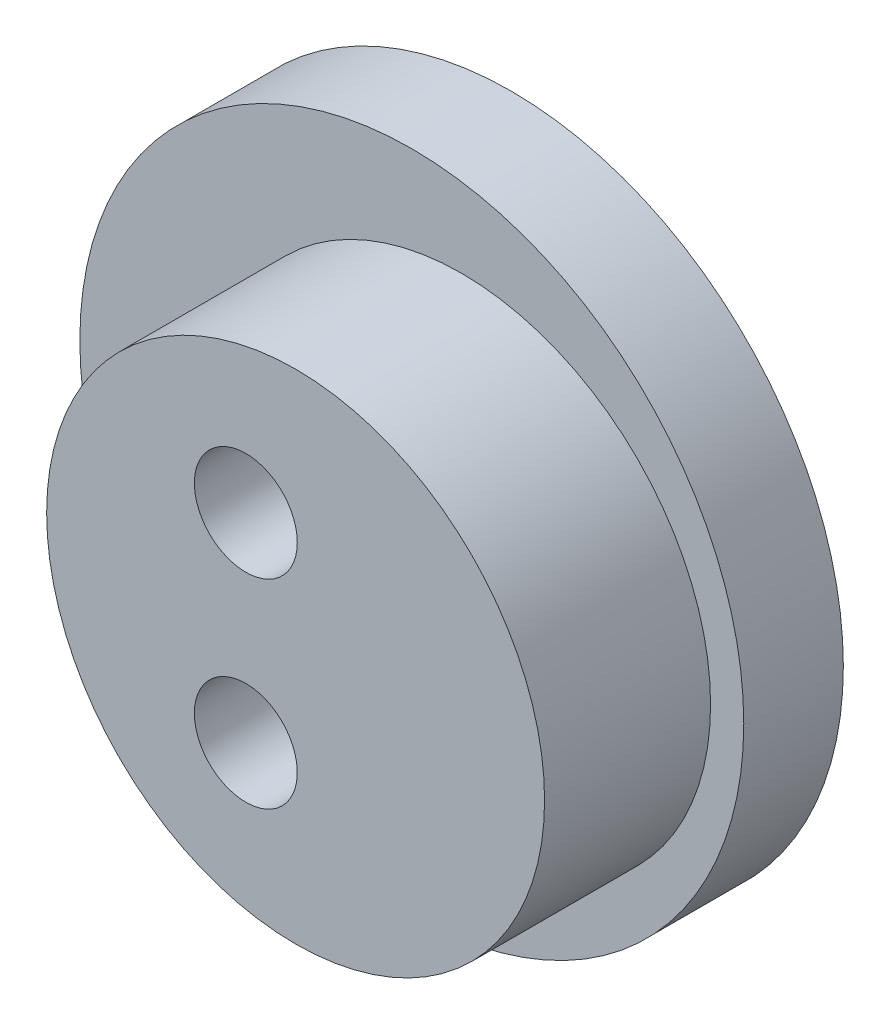
SolidWorks part; units mm, degrees
ref_plane "Front Plane" through (0, 0, 0) normal (0, 0, 1) x (1, 0, 0)
ref_plane "Top Plane" through (0, 0, 0) normal (0, 1, 0) x (1, 0, 0)
ref_plane "Right Plane" through (0, 0, 0) normal (1, 0, 0) x (0, 0, -1)
sketch "Sketch1" plane through (0, 0, 0) normal (0, 0, 1) x (1, 0, 0)
  circle A0 centre (0, 0) radius 10
  dimension "D1" = 20
extrude "Boss-Extrude1" add sketch "Sketch1" along normal blind 3
sketch "Sketch2" plane through (0, 0, 3) normal (0, 0, 1) x (1, 0, 0)
  line L0 (0, 0) -> (14.2373, 0) construction
  circle A0 centre (1.5, 0) radius 7.5
  point P3 (1.5, 0)
  dimension "D2" = 15
  dimension "D1" = 1.5
extrude "Boss-Extrude2" add sketch "Sketch2" along normal blind 5
sketch "Sketch3" plane through (0, 0, 8) normal (0, 0, 1) x (1, 0, 0)
  line L0 (0, 11.0707) -> (0, -11.3162) construction
  line L1 (0, 10.9234) -> (0, -11.3162) construction
  line L2 (0, 0) -> (12.3717, 0) construction
  circle A0 centre (0, 3) radius 1.55
  circle A1 centre (0, -3) radius 1.55
  point P9 (0, 0)
  dimension "D2" = 3.1
  dimension "D1" = 0
  dimension "D3" = 3
extrude "Cut-Extrude1" cut sketch "Sketch3" against normal through all
